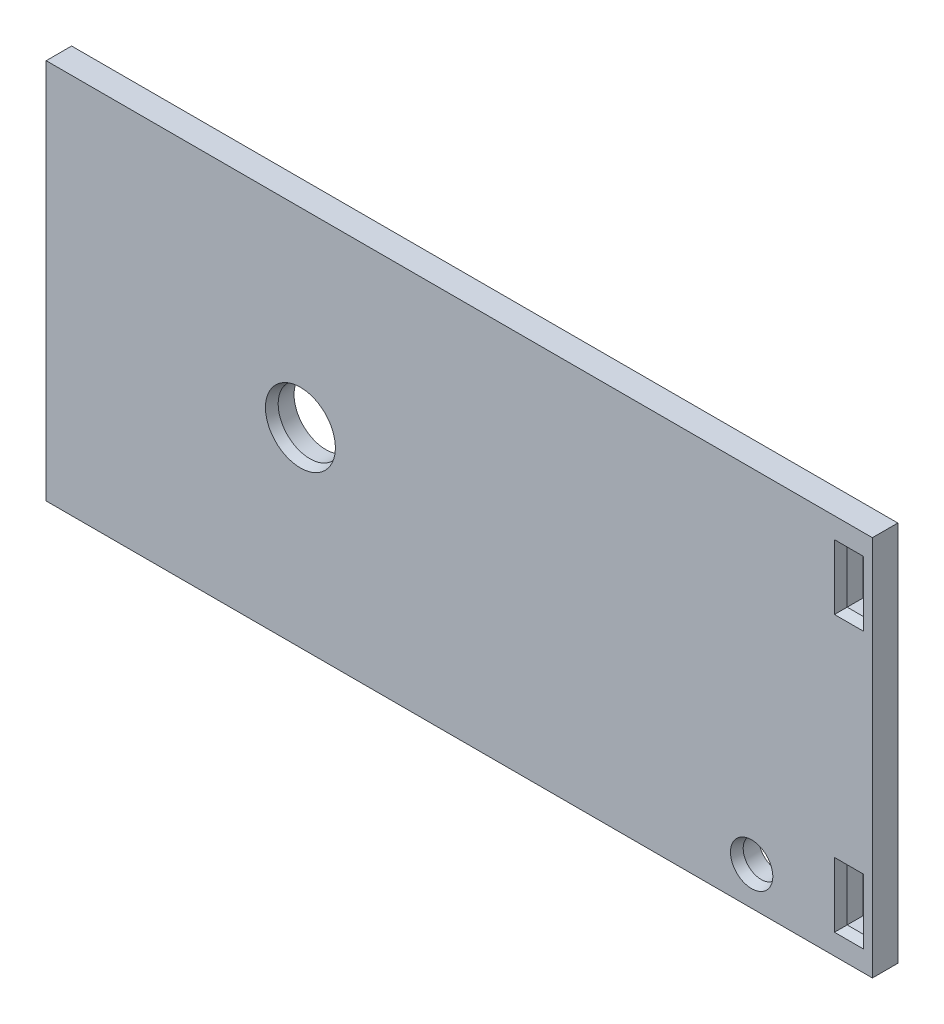
SolidWorks part; units mm, degrees
ref_plane "Front Plane" through (0, 0, 0) normal (0, 0, 1) x (1, 0, 0)
ref_plane "Top Plane" through (0, 0, 0) normal (0, 1, 0) x (1, 0, 0)
ref_plane "Right Plane" through (0, 0, 0) normal (1, 0, 0) x (0, 0, -1)
sketch "Sketch1" plane through (0, 0, 0) normal (0, 0, 1) x (1, 0, 0)
  line L2 (-65, -30) -> (-65, 30)
  line L12 (61.3, 26.25) -> (61.3, 17.05) construction
  line L13 (-65, 30) -> (65, 30)
  line L15 (-65, -30) -> (65, -30)
  line L16 (65, 30) -> (65, -30)
  line L17 (59.535, 26.25) -> (63.065, 26.25)
  line L18 (59.535, 26.25) -> (59.535, 17.05)
  line L19 (59.535, 17.05) -> (63.065, 17.05)
  line L20 (63.065, 26.25) -> (63.065, 17.05)
  line L21 (59.535, -17.05) -> (63.065, -17.05)
  line L22 (59.535, -17.05) -> (59.535, -26.25)
  line L23 (59.535, -26.25) -> (63.065, -26.25)
  line L24 (63.065, -17.05) -> (63.065, -26.25)
  line L25 (61.3, -17.05) -> (61.3, -26.25) construction
  line L26 (63.065, 21.65) -> (59.535, 21.65) construction
  line L27 (63.065, -21.65) -> (59.535, -21.65) construction
  circle A3 centre (-25, 0) radius 5
  circle A4 centre (46, -24) radius 2.83
  circle A6 centre (16, 0) radius 7 construction
  point P2 (0, 30)
  point P9 (65, 0)
  dimension "D6" = 10
  dimension "D4" = 5.66
  dimension "D14" = 14
  dimension "D2" = 60
  dimension "D3" = 130
  dimension "D8" = 24
  dimension "D1" = 9.2
  dimension "D9" = 3.53
  dimension "D10" = 21.65
  dimension "D11" = 21.65
  dimension "D5" = 40
  dimension "D7" = 86.3
  dimension "D12" = 71
  dimension "D13" = 41
extrude "Boss-Extrude1" add sketch "Sketch1" along normal mid plane 4
chamfer "Chamfer1" distance 0.5 distance2 1.5 10 edges at (61.3, 17.05, 2) (59.535, 21.65, 2) (61.3, 26.25, 2) (63.065, 21.65, 2) (-20, 0, 2) (48.83, -24, 2) (61.3, -26.25, 2) (59.535, -21.65, 2) (61.3, -17.05, 2) (63.065, -21.65, 2)
sketch "Sketch3" plane through (0, 0, -2) normal (0, 0, -1) x (-1, 0, 0)
  line L0 (-61.3, 26.25) -> (-61.3, 17.05) construction
  line L1 (-63.065, 21.65) -> (-59.535, 21.65) construction
  line L2 (-61.3, -17.05) -> (-61.3, -26.25) construction
  line L3 (-59.535, -17.05) -> (-63.065, -17.05) construction
  line L4 (-63.065, -21.65) -> (-59.535, -21.65) construction
equation "\"hole_width\"=3.4"
equation "\"hole_length\"=8.7"
equation "\"pin_hole_height\"=9.2"
equation "\"D1@Sketch1\"=\"pin_hole_height\""
equation "\"pin_hole_width\"=3.53"
equation "\"D9@Sketch1\"=\"pin_hole_width\""
equation "\"wall_thick_ness\"=4"
equation "\"D1@Boss-Extrude1\"=\"wall_thick_ness\""
equation "\"back_boost\"= 7"
equation "\"D5@Sketch1\"=\"back_boost\"+33.00mm"
equation "\"D3@Sketch1\"=123.00mm+\"back_boost\""
